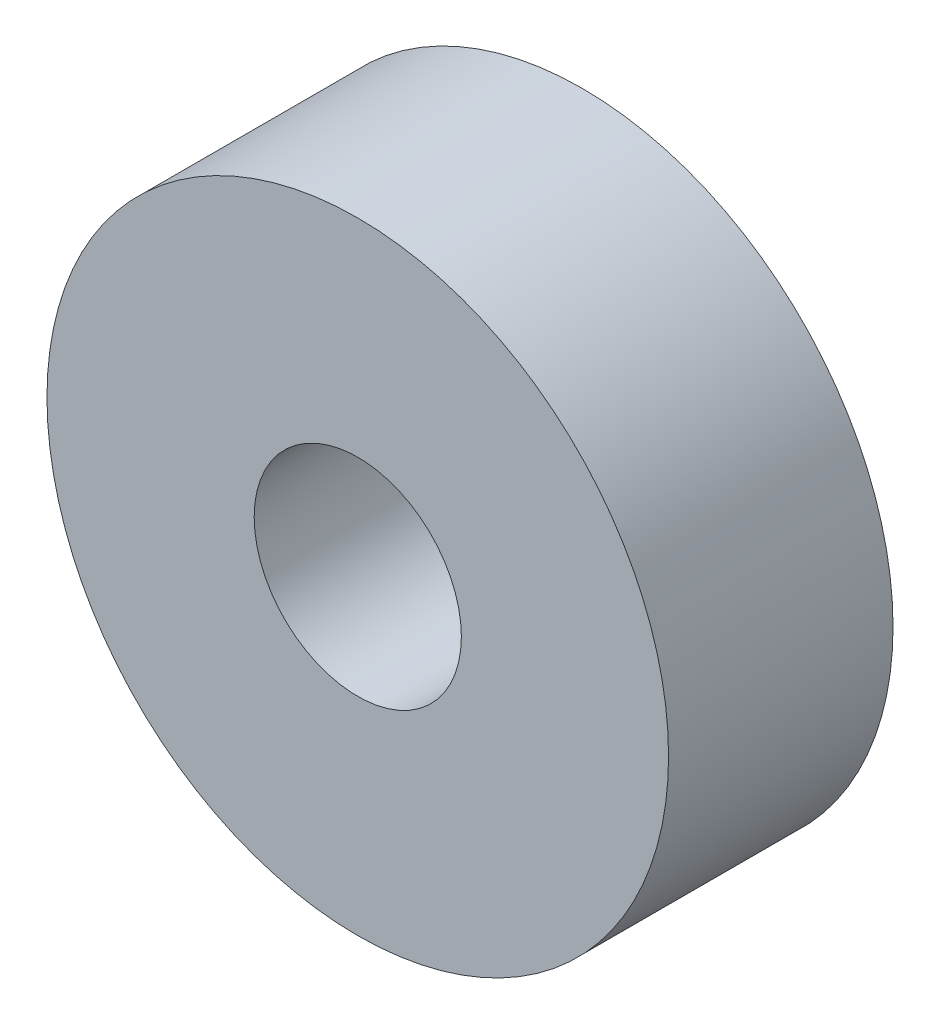
SolidWorks part; units mm, degrees
ref_plane "Спереди" through (0, 0, 0) normal (0, 0, 1) x (1, 0, 0)
ref_plane "Сверху" through (0, 0, 0) normal (0, 1, 0) x (1, 0, 0)
ref_plane "Справа" through (0, 0, 0) normal (1, 0, 0) x (0, 0, -1)
sketch "Эскиз1" plane through (0, 0, 0) normal (0, 0, 1) x (1, 0, 0)
  circle A0 centre (0, 0) radius 3
  circle A1 centre (0, 0) radius 9
extrude "Вытянуть2" add sketch "Эскиз1" along normal blind 6.5
